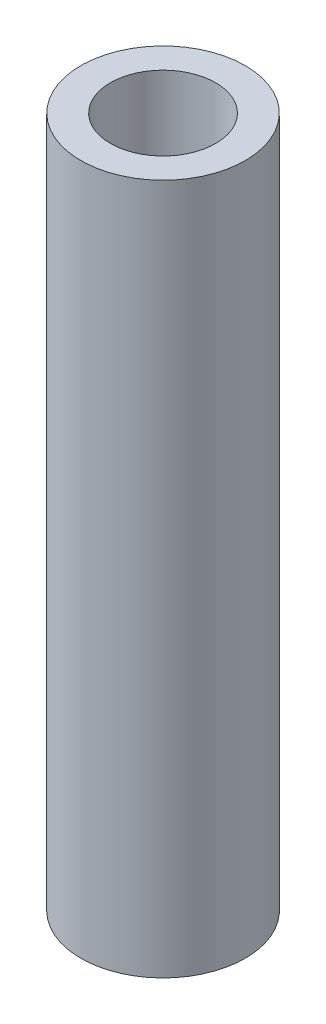
SolidWorks part; units mm, degrees
material "ABS"
ref_plane "Front Plane" through (0, 0, 0) normal (0, 0, 1) x (1, 0, 0)
ref_plane "Top Plane" through (0, 0, 0) normal (0, 1, 0) x (1, 0, 0)
ref_plane "Right Plane" through (0, 0, 0) normal (1, 0, 0) x (0, 0, -1)
sketch "Sketch1" plane through (0, 0, 0) normal (0, 1, 0) x (1, 0, 0)
  circle A0 centre (0, 0) radius 2.5
  dimension "D1" = 5
extrude "Boss-Extrude1" add sketch "Sketch1" along normal mid plane 21
hole_wizard "M3 Clearance Hole1" positions "Sketch2" profile "Sketch3" hole size "M3" standard "ANSI Metric" end condition through all
sketch "Sketch2" plane through (0, 10.5, 0) normal (0, 1, 0) x (1, 0, 0)
  point P0 (0, 0)
sketch "Sketch3" plane through (0, 10.5, 0) normal (1, 0, 0) x (0, 0, 1)
  line L0 (0, 0) -> (0, 21)
  line L1 (0, 21) -> (1.6, 21)
  line L2 (1.6, 21) -> (1.6, 0)
  line L5 (1.6, 0) -> (0, 0)
  line L11 (0, -6.35) -> (0, 107.95) construction
  dimension "Thru Hole Dia." = 3.2
  dimension "Thru Hole Depth" = 21
